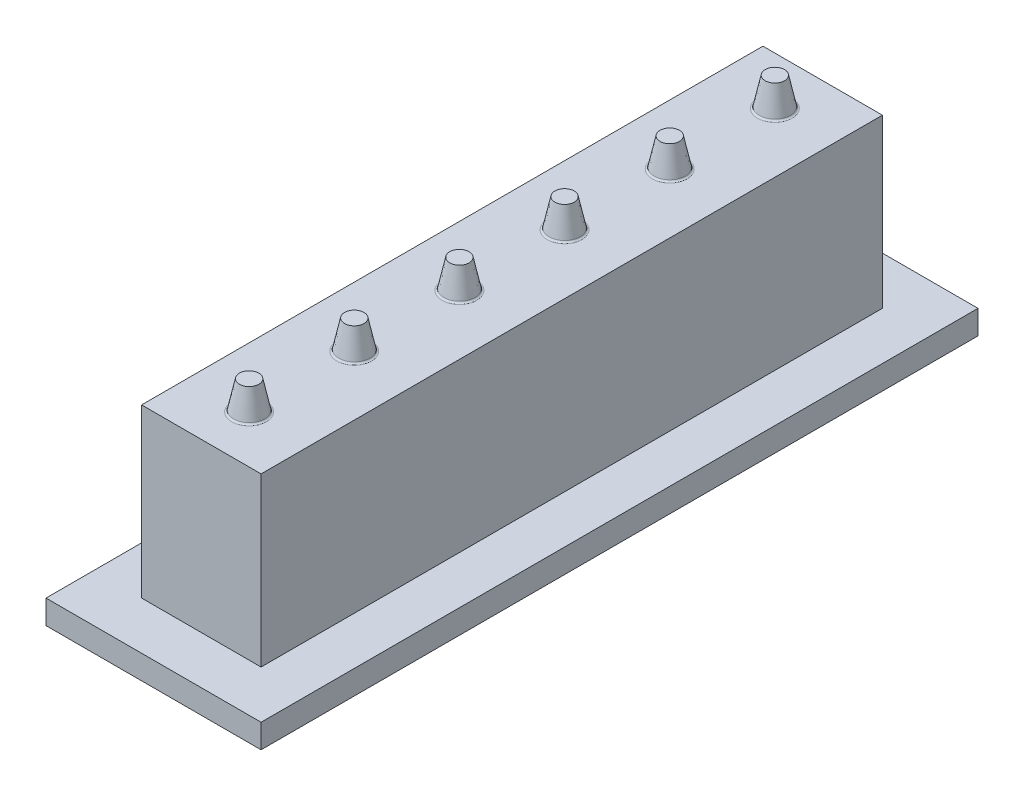
SolidWorks part; units mm, degrees
ref_plane "Front Plane" through (0, 0, 0) normal (0, 0, 1) x (1, 0, 0)
ref_plane "Top Plane" through (0, 0, 0) normal (0, 1, 0) x (1, 0, 0)
ref_plane "Right Plane" through (0, 0, 0) normal (1, 0, 0) x (0, 0, -1)
sketch "Sketch1" plane through (0, 0, 0) normal (0, 0, 1) x (1, 0, 0)
  line L1 (0, 0) -> (31.75, 0)
  line L2 (0, 0) -> (0, 50.8)
  line L3 (0, 50.8) -> (31.75, 50.8)
  line L4 (31.75, 0) -> (31.75, 50.8)
  dimension "D1" = 31.75
  dimension "D2" = 50.8
extrude "Boss-Extrude1" add sketch "Sketch1" along normal blind 165.1
sketch "Sketch2" plane through (0, 50.8, 0) normal (0, 1, 0) x (1, 0, 0)
  line L0 (15.875, -12.7) -> (31.75, -12.7) construction
  line L1 (31.75, -165.1) -> (31.75, 0) construction
  line L2 (15.875, -12.7) -> (0, -12.7) construction
  line L3 (0, -165.1) -> (0, 0) construction
  line L4 (31.75, 0) -> (0, 0) construction
  line L6 (15.875, -12.7) -> (15.875, -40.64) construction
  line L7 (15.875, -40.64) -> (15.875, -68.58) construction
  line L8 (15.875, -68.58) -> (15.875, -96.52) construction
  line L9 (15.875, -96.52) -> (15.875, -124.46) construction
  line L10 (15.875, -124.46) -> (15.875, -152.4) construction
  line L11 (31.75, -165.1) -> (0, -165.1) construction
  circle A0 centre (15.875, -12.7) radius 4.191
  circle A1 centre (15.875, -40.64) radius 4.191
  circle A2 centre (15.875, -68.58) radius 4.191
  circle A3 centre (15.875, -96.52) radius 4.191
  circle A4 centre (15.875, -124.46) radius 4.191
  circle A5 centre (15.875, -152.4) radius 4.191
  dimension "D1" = 8.382
  dimension "D2" = 12.7
  dimension "D3" = 12.7
extrude "Boss-Extrude2" add sketch "Sketch2" along normal blind 7.62 draft 12
fillet "Fillet2" radius 0.508 6 edges at (15.875, 50.8, 120.269) (15.875, 50.8, 148.209) (15.875, 50.8, 92.329) (15.875, 50.8, 64.389) (15.875, 50.8, 36.449) (15.875, 50.8, 8.509)
sketch "Sketch3" plane through (0, 0, 0) normal (0, -1, 0) x (-1, 0, 0)
  line L0 (0, -165.1) -> (0, 0) construction
  line L1 (-6.35, -6.35) -> (-25.4, -6.35)
  line L2 (-6.35, -6.35) -> (-6.35, -158.75)
  line L3 (-6.35, -158.75) -> (-25.4, -158.75)
  line L4 (-25.4, -6.35) -> (-25.4, -158.75)
  line L5 (0, 0) -> (-31.75, 0) construction
  line L6 (0, -165.1) -> (-31.75, -165.1) construction
  line L7 (-31.75, -165.1) -> (-31.75, 0) construction
  dimension "D1" = 6.35
  dimension "D2" = 6.35
  dimension "D3" = 6.35
  dimension "D4" = 6.35
extrude "Cut-Extrude1" cut sketch "Sketch3" against normal blind 44.45
sketch "Sketch4" plane through (0, 0, 0) normal (0, -1, 0) x (-1, 0, 0)
  line L1 (0, 0) -> (-31.75, 0)
  line L2 (0, 0) -> (0, -165.1)
  line L3 (0, -165.1) -> (-31.75, -165.1)
  line L4 (-31.75, 0) -> (-31.75, -165.1)
  line L5 (12.7, 12.7) -> (-44.45, 12.7)
  line L6 (12.7, 12.7) -> (12.7, -177.8)
  line L7 (12.7, -177.8) -> (-44.45, -177.8)
  line L8 (-44.45, 12.7) -> (-44.45, -177.8)
  point P10 (-15.875, -177.8)
  dimension "D1" = 12.7
  dimension "D2" = 12.7
  dimension "D3" = 12.7
  dimension "D4" = 12.7
extrude "Boss-Extrude3" add sketch "Sketch4" against normal blind 6.35
